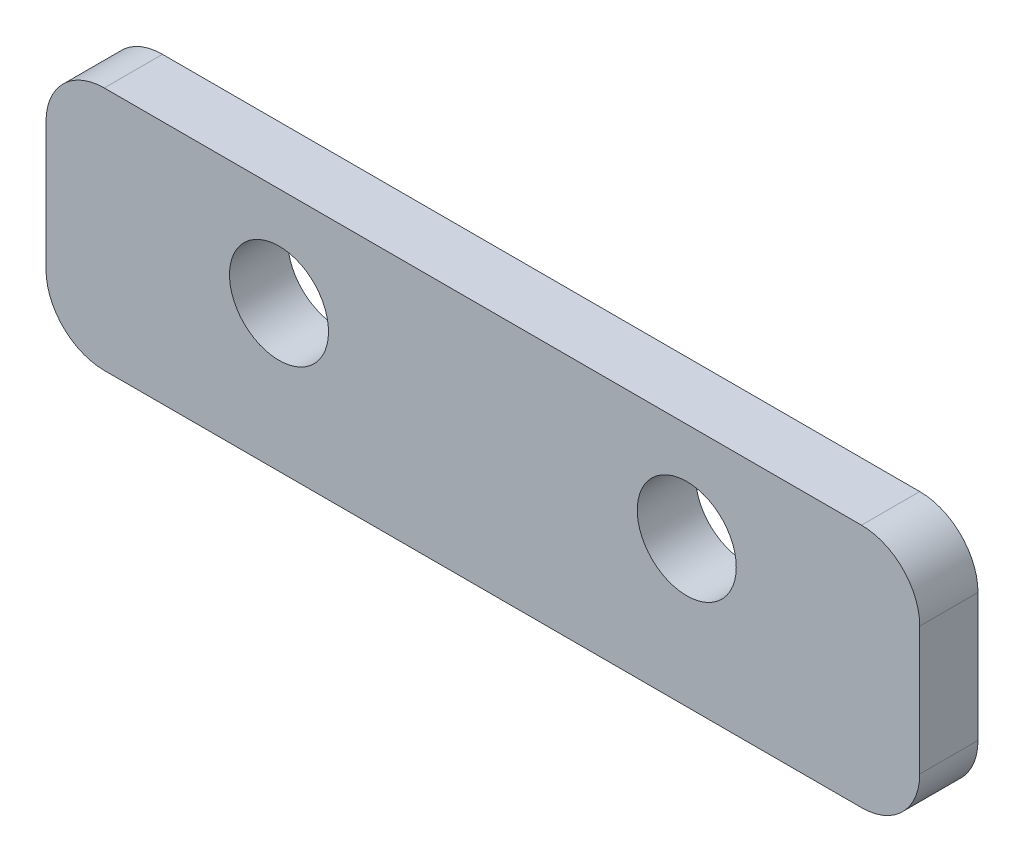
SolidWorks part; units mm, degrees
material "AISI 1020"
ref_plane "Front Plane" through (0, 0, 0) normal (0, 0, 1) x (1, 0, 0)
ref_plane "Top Plane" through (0, 0, 0) normal (0, 1, 0) x (1, 0, 0)
ref_plane "Right Plane" through (0, 0, 0) normal (1, 0, 0) x (0, 0, -1)
sketch "Sketch1" plane through (0, 0, 0) normal (0, 0, 1) x (1, 0, 0)
  line L1 (-15, -5) -> (15, -5)
  line L2 (-15, -5) -> (-15, 5)
  line L3 (-15, 5) -> (15, 5)
  line L4 (15, -5) -> (15, 5)
  line L5 (-15, -5) -> (15, 5) construction
  line L6 (-15, 5) -> (15, -5) construction
  point P0 (0, 0)
  dimension "D1" = 10
  dimension "D2" = 30
extrude "Boss-Extrude1" add sketch "Sketch1" along normal blind 2
hole_wizard "M3 Clearance Hole1" positions "Sketch2" profile "Sketch3" hole size "M3" standard "ANSI Metric" end condition through all
sketch "Sketch2" plane through (0, 0, 2) normal (0, 0, 1) x (1, 0, 0)
  line L0 (15, 5) -> (-15, 5) construction
  point P0 (-7, 0)
  point P2 (7, 0)
  dimension "D1" = 7
  dimension "D2" = 7
  dimension "D3" = 5
  dimension "D4" = 5
sketch "Sketch3" plane through (-7, 0, 2) normal (1, 0, 0) x (0, -1, 0)
  line L0 (0, 0) -> (0, 2)
  line L1 (0, 2) -> (1.7, 2)
  line L2 (1.7, 2) -> (1.7, 0)
  line L5 (1.7, 0) -> (0, 0)
  line L11 (0, -6.35) -> (0, 107.95) construction
  dimension "Thru Hole Dia." = 3.4
  dimension "Thru Hole Depth" = 2
sketch "Sketch4" plane through (0, -5, 0) normal (0, -1, 0) x (1, 0, 0)
  line L0 (-15, 2) -> (15, 2) construction
  line L1 (16.6361, 0) -> (-17.8659, 0)
  line L2 (16.6361, 0) -> (16.6361, 2)
  line L3 (16.6361, 2) -> (-17.8659, 2)
  line L4 (-17.8659, 0) -> (-17.8659, 2)
  line L5 (-15, 0) -> (15, 0) construction
sketch "Sketch5" plane through (0, 5, 0) normal (0, 1, 0) x (1, 0, 0)
  line L1 (15, 0) -> (-15, 0)
  line L2 (15, 0) -> (15, -2)
  line L3 (15, -2) -> (-15, -2)
  line L4 (-15, 0) -> (-15, -2)
extrude "Cut-Extrude1" cut sketch "Sketch5" against normal blind 1.6
fillet "Fillet1" radius 2 4 edges at (15, -5, 1) (-15, -5, 1) (-15, 3.4, 1) (15, 3.4, 1)
